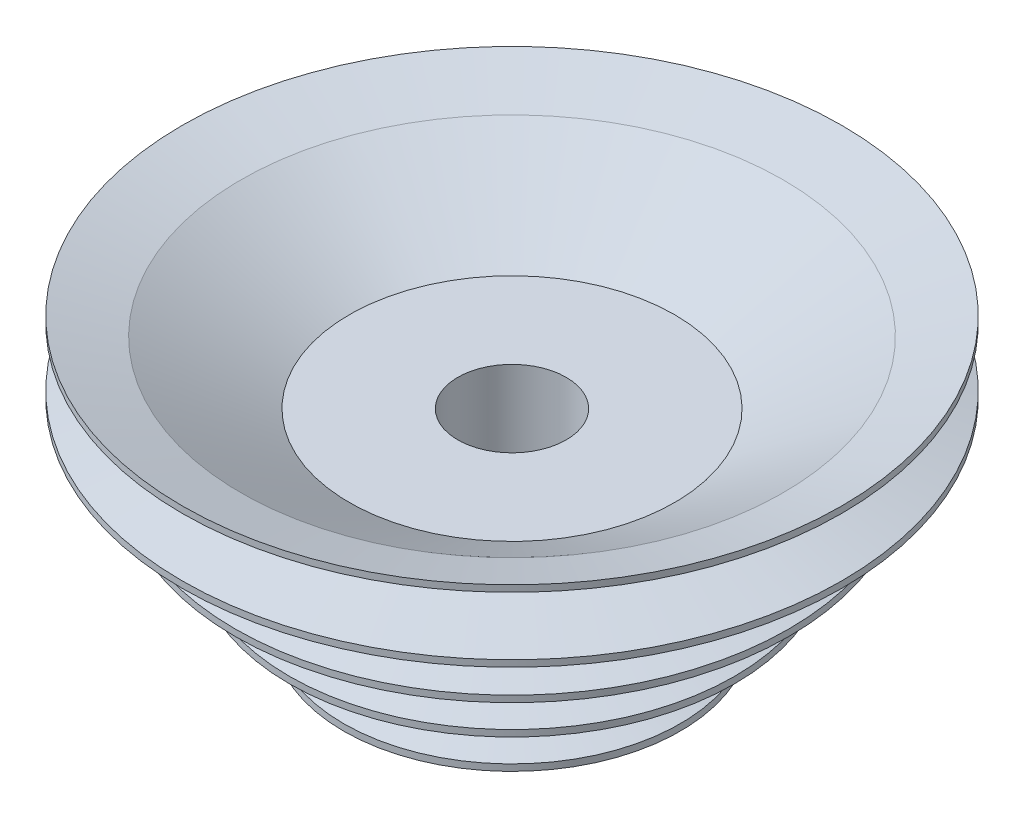
SolidWorks part; units mm, degrees
ref_plane "Front Plane" through (0, 0, 0) normal (0, 0, 1) x (1, 0, 0)
ref_plane "Top Plane" through (0, 0, 0) normal (0, 1, 0) x (1, 0, 0)
ref_plane "Right Plane" through (0, 0, 0) normal (1, 0, 0) x (0, 0, -1)
sketch "Sketch1" plane through (0, 0, 0) normal (0, 0, 1) x (1, 0, 0)
  line L0 (63.8, 32.9) -> (50, 37.1191)
  line L1 (12.5, 0) -> (38.8, 0)
  line L2 (12.5, 0) -> (12.5, 45)
  line L3 (38.8, 0) -> (38.8, 1.5)
  line L4 (38.8, 1.5) -> (25, 5.7191)
  line L5 (38.8, 14.2) -> (38.8, 15.7)
  line L6 (38.8, 1.5) -> (38.8, 14.2)
  line L7 (38.8, 14.2) -> (25, 9.9809)
  line L8 (25, 9.9809) -> (25, 5.7191)
  line L9 (51.3, 29.9) -> (51.3, 31.4)
  line L10 (51.3, 31.4) -> (63.8, 31.4)
  line L11 (51.3, 15.7) -> (51.3, 17.2)
  line L12 (38.8, 15.7) -> (51.3, 15.7)
  line L13 (51.3, 17.2) -> (37.5, 21.4191)
  line L14 (63.8, 31.4) -> (63.8, 32.9)
  line L15 (51.3, 29.9) -> (37.5, 25.6809)
  line L16 (37.5, 25.6809) -> (37.5, 21.4191)
  line L17 (50, 41.3809) -> (63.8, 45.6)
  line L18 (50, 41.3809) -> (50, 37.1191)
  line L19 (63.8, 45.6) -> (63.8, 47.1)
  line L20 (63.8, 47.1) -> (76, 47.1)
  line L21 (76, 47.1) -> (76, 48.6)
  line L22 (76, 48.6) -> (62.5, 52.7274)
  line L23 (76, 62.0611) -> (76, 63.5611)
  line L24 (62.5, 57.9338) -> (62.5, 52.7274)
  line L25 (76, 63.5611) -> (62.5, 59.4338)
  line L26 (76, 62.0611) -> (62.5, 57.9338)
  line L27 (12.5, 45) -> (37.5, 45)
  line L28 (37.5, 45) -> (62.5, 59.4338)
  line L29 (0, 0) -> (0, 75.0856) construction
  dimension "D1" = 45
  dimension "D2" = 12.5
  dimension "D3" = 25
  dimension "D4" = 13.8
  dimension "D5" = 1.5
  dimension "D6" = 12.7
  dimension "D7" = 34
  dimension "D8" = 37.5
  dimension "D9" = 50
  dimension "D10" = 30
  dimension "D11" = 62.5
  dimension "D12" = 76
  dimension "D13" = 17
revolve "Revolve1" add sketch "Sketch1" angle 360 about L29
